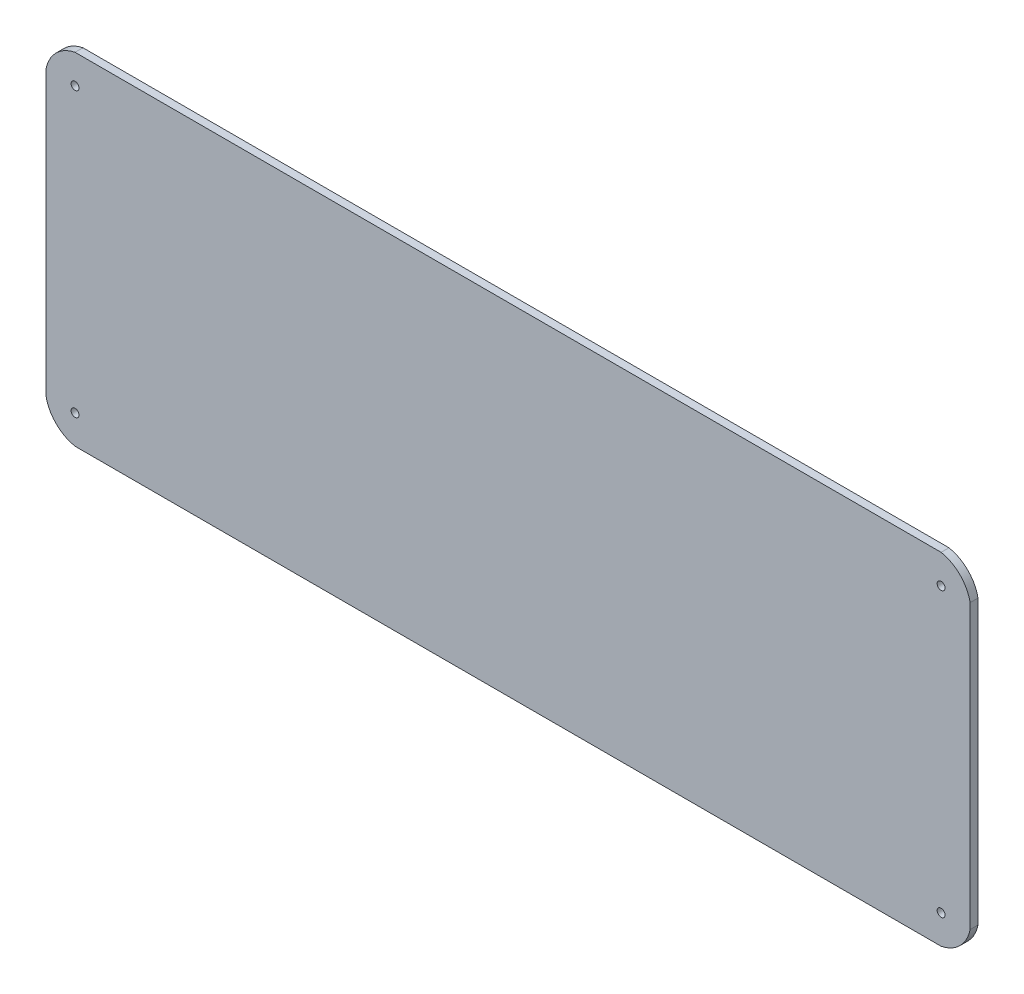
SolidWorks part; units mm, degrees
ref_plane "Alzado" through (0, 0, 0) normal (0, 0, 1) x (1, 0, 0)
ref_plane "Planta" through (0, 0, 0) normal (0, 1, 0) x (1, 0, 0)
ref_plane "Vista lateral" through (0, 0, 0) normal (1, 0, 0) x (0, 0, -1)
sketch "Model" plane through (0, 0, 0) normal (0, 0, 1) x (1, 0, 0)
  line L0 (-175.63, 53.7525) -> (-175.63, -54.1267)
  line L1 (-164.5696, 64.8129) -> (165.4304, 64.8129)
  line L2 (176.4908, 53.7525) -> (176.4908, -54.1267)
  line L3 (165.4304, -65.1871) -> (-164.5696, -65.1871)
  arc A0 (-164.5696, 64.8129) -> (-175.63, 53.7525) centre (-161.889, 51.0719) ccw
  arc A1 (176.4908, 53.7525) -> (165.4304, 64.8129) centre (162.7498, 51.0719) ccw
  arc A2 (-175.63, -54.1267) -> (-164.5696, -65.1871) centre (-161.889, -51.4461) ccw
  arc A3 (165.4304, -65.1871) -> (176.4908, -54.1267) centre (162.7498, -51.4461) ccw
  circle A4 centre (-164.5696, 53.7525) radius 1.5
  circle A5 centre (-164.5696, -54.1542) radius 1.5
  circle A6 centre (165.4304, -54.1267) radius 1.5
  circle A7 centre (165.4304, 53.7525) radius 1.5
  point P20 (-175.63, -0.1871)
  point P21 (0.4304, 64.8129)
extrude "Saliente-Extruir1" add sketch "Model" along normal blind 3
